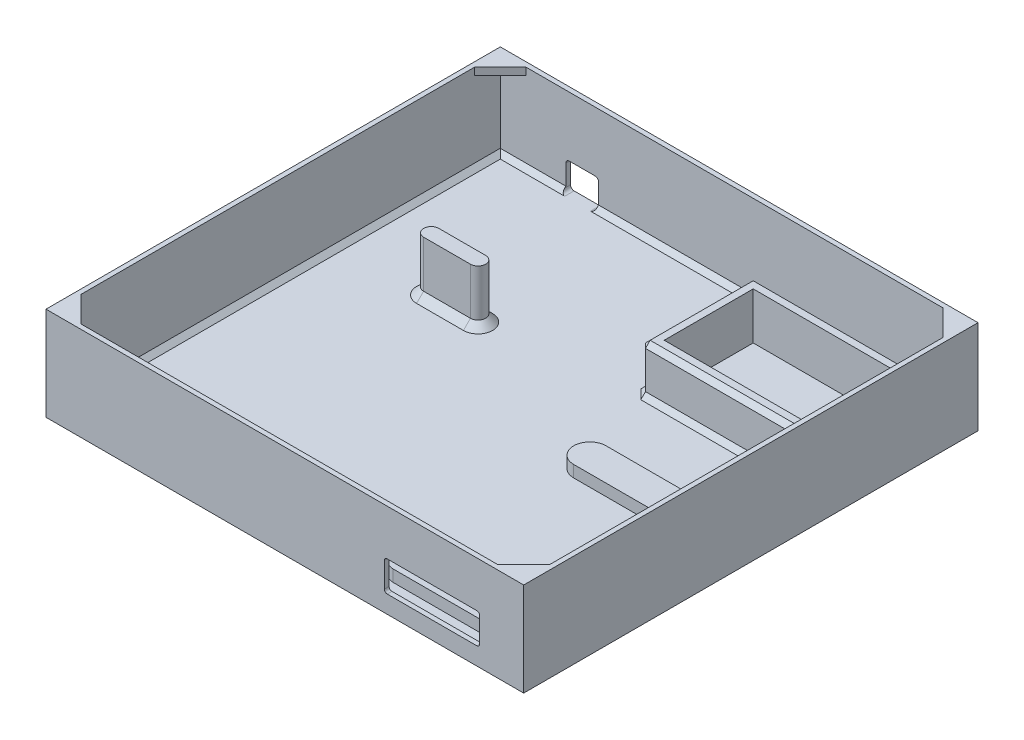
SolidWorks part; units mm, degrees
ref_plane "Ön Düzlem" through (0, 0, 0) normal (0, 0, 1) x (1, 0, 0)
ref_plane "Üst Düzlem" through (0, 0, 0) normal (0, 1, 0) x (1, 0, 0)
ref_plane "Sağ Düzlem" through (0, 0, 0) normal (1, 0, 0) x (0, 0, -1)
sketch "Çizim1" plane through (0, 0, 0) normal (0, 1, 0) x (1, 0, 0)
  line L6 (-102, 97) -> (102, 97)
  line L11 (-102, 97) -> (-102, -97)
  line L12 (-102, -97) -> (102, -97)
  line L17 (102, 97) -> (102, -97)
  line L18 (-102, 97) -> (102, -97) construction
  line L23 (-102, -97) -> (102, 97) construction
  point P0 (0, 0)
  dimension "D1" = 204
  dimension "D2" = 194
extrude "Yükseklik-Ekstrüzyon2" add sketch "Çizim1" along normal blind 40 contours L11 L12 L17 L6
sketch "Çizim3" plane through (0, 40, 0) normal (0, 1, 0) x (1, 0, 0)
  line L1 (-100, 95) -> (100, 95)
  line L2 (-100, 95) -> (-100, -95)
  line L3 (-100, -95) -> (100, -95)
  line L4 (100, 95) -> (100, -95)
  line L5 (-100, 95) -> (100, -95) construction
  line L6 (-100, -95) -> (100, 95) construction
  point P0 (0, 0)
  dimension "D1" = 190
  dimension "D2" = 200
extrude "Kes-Ekstrüzyon2" cut sketch "Çizim3" against normal blind 37.5 contours L2 L3 L4 L1
sketch "Çizim4" plane through (0, 2.5, 0) normal (0, 1, 0) x (1, 0, 0)
  line L0 (-102, 97) -> (-102, -97) construction
  line L1 (-102, -97) -> (102, -97) construction
  line L2 (-62.5, 24.75) -> (-42.5, 24.75)
  line L3 (-62.5, 31.25) -> (-42.5, 31.25)
  line L4 (-42.5, 28) -> (-42.5, -84) construction
  line L5 (-62.5, -87.25) -> (-42.5, -87.25)
  line L6 (-75.9536, -28) -> (-42.5, -28) construction
  line L7 (-62.5, -80.75) -> (-42.5, -80.75)
  arc A5 (-62.5, 31.25) -> (-62.5, 24.75) centre (-62.5, 28) ccw
  arc A7 (-42.5, 24.75) -> (-42.5, 31.25) centre (-42.5, 28) ccw
  arc A10 (-42.5, -80.75) -> (-42.5, -87.25) centre (-42.5, -84) cw
  arc A11 (-62.5, -87.25) -> (-62.5, -80.75) centre (-62.5, -84) cw
  dimension "D3" = 20
  dimension "D4" = 121.75
  dimension "D5" = 6.5
  dimension "D11" = 6.5
  dimension "D12" = 6.5
  dimension "D14" = 20
  dimension "D15" = 3.25
  dimension "D1" = 39.5
  dimension "D2" = 13
extrude "Yükseklik-Ekstrüzyon3" add sketch "Çizim4" along normal blind 23
sketch "Çizim6" plane through (0, 2.5, 0) normal (0, 1, 0) x (1, 0, 0)
  line L0 (-102, 97) -> (102, 97) construction
  line L1 (24, 79) -> (84, 79)
  line L2 (24, 79) -> (24, 41)
  line L3 (24, 41) -> (84, 41)
  line L4 (84, 79) -> (84, 41)
  line L5 (24, 79) -> (84, 41) construction
  line L6 (24, 41) -> (84, 79) construction
  line L7 (19, 84) -> (89, 84)
  line L8 (19, 84) -> (19, 36)
  line L9 (19, 36) -> (89, 36)
  line L10 (89, 84) -> (89, 36)
  line L11 (19, 84) -> (89, 36) construction
  line L12 (19, 36) -> (89, 84) construction
  line L13 (102, 97) -> (102, -97) construction
  point P0 (54, 60)
  point P5 (54, 60)
  dimension "D1" = 38
  dimension "D2" = 60
  dimension "D3" = 70
  dimension "D4" = 5
  dimension "D5" = 13
  dimension "D6" = 13
extrude "Yükseklik-Ekstrüzyon4" add sketch "Çizim6" along normal blind 20
sketch "Çizim7" plane through (0, 2.5, 0) normal (0, 1, 0) x (1, 0, 0)
  line L0 (-102, -97) -> (102, -97) construction
  line L1 (87, -97) -> (33, -97) construction
  line L5 (35.6, -9.25) -> (84.4, -9.25)
  line L8 (84.4, 4.55) -> (35.6, 4.55)
  line L10 (35.6, -77.25) -> (84.4, -77.25)
  line L12 (84.4, -86.45) -> (35.6, -86.45)
  arc A8 (35.6, 4.55) -> (35.6, -9.25) centre (35.6, -2.35) ccw
  arc A9 (84.4, -9.25) -> (84.4, 4.55) centre (84.4, -2.35) ccw
  arc A10 (35.6, -77.25) -> (35.6, -86.45) centre (35.6, -81.85) ccw
  arc A11 (84.4, -86.45) -> (84.4, -77.25) centre (84.0289, -81.85) ccw
  point P2 (83.6578, -86.45)
  point P6 (83.6578, -86.45)
  dimension "D3" = 0
extrude "Yükseklik-Ekstrüzyon7" add sketch "Çizim7" along normal blind 5
sketch "Çizim8" plane through (0, 40, 0) normal (0, 1, 0) x (1, 0, 0)
  line L0 (-102, 97) -> (-102, 82)
  line L1 (-102, 97) -> (-102, -97) construction
  line L2 (-102, 82) -> (-87, 97)
  line L3 (-102, 97) -> (102, 97) construction
  line L4 (-102, 97) -> (-87, 97)
  line L5 (0, 0) -> (166.3911, 0) construction
  line L7 (0, 122.3397) -> (0, 0) construction
  line L8 (102, 97) -> (87, 97)
  line L9 (102, 82) -> (87, 97)
  line L10 (102, 97) -> (102, 82)
  line L11 (102, -97) -> (102, -82)
  line L12 (102, -82) -> (87, -97)
  line L13 (102, -97) -> (87, -97)
  line L14 (-102, -97) -> (-87, -97)
  line L15 (-102, -82) -> (-87, -97)
  line L16 (-102, -97) -> (-102, -82)
  point P21 (0, 0)
  point P22 (0, 0)
  dimension "D1" = 15
  dimension "D2" = 15
extrude "Yükseklik-Ekstrüzyon8" add sketch "Çizim8" against normal blind 3
sketch "Çizim9" plane through (0, 0, 97) normal (0, 0, 1) x (1, 0, 0)
  line L6 (-102, 40) -> (-102, 0) construction
  line L7 (43.7, 7.5) -> (82, 7.5)
  line L8 (42.5, 8.7) -> (42.5, 19.3)
  line L9 (43.7, 20.5) -> (82, 20.5)
  line L10 (83.2, 8.7) -> (83.2, 19.3)
  line L11 (-102, 0) -> (102, 0) construction
  arc A4 (82, 20.5) -> (83.2, 19.3) centre (82, 19.3) cw
  arc A5 (83.2, 8.7) -> (82, 7.5) centre (82, 8.7) cw
  arc A6 (43.7, 7.5) -> (42.5, 8.7) centre (43.7, 8.7) cw
  arc A7 (42.5, 19.3) -> (43.7, 20.5) centre (43.7, 19.3) cw
  dimension "D4" = 40.7
  dimension "D5" = 1.2
  dimension "D1" = 144.5
  dimension "D2" = 7.5
  dimension "D3" = 13
extrude "Kes-Ekstrüzyon5" cut sketch "Çizim9" against normal blind 3
sketch "Çizim11" plane through (0, 0, -97) normal (0, 0, -1) x (-1, 0, 0)
  line L0 (102, 40) -> (102, 0) construction
  line L1 (59.5, 2.5) -> (70.5, 2.5)
  line L2 (58, 4) -> (58, 13)
  line L3 (59.5, 14.5) -> (70.5, 14.5)
  line L4 (72, 4) -> (72, 13)
  line L5 (102, 0) -> (-102, 0) construction
  arc A0 (70.5, 2.5) -> (72, 4) centre (70.5, 4) ccw
  arc A1 (58, 13) -> (59.5, 14.5) centre (59.5, 13) cw
  arc A2 (70.5, 14.5) -> (72, 13) centre (70.5, 13) cw
  arc A3 (59.5, 2.5) -> (58, 4) centre (59.5, 4) cw
  point P10 (72, 2.5)
  point P13 (58, 14.5)
  point P16 (72, 14.5)
  dimension "D5" = 1.5
  dimension "D1" = 14
  dimension "D2" = 12
  dimension "D3" = 30
  dimension "D4" = 2.5
extrude "Kes-Ekstrüzyon7" cut sketch "Çizim11" against normal blind 3
chamfer "Pah1" distance 2 angle 45 19 edges at (0, 2.5, 95) (-100, 2.5, 0) (-85.25, 2.5, -95) (100, 2.5, 0) (20.25, 2.5, -95) (-58.4393, 2.9393, -95) (-71.5607, 2.9393, -95) (89, 22.5, -60) (54, 22.5, -84) (19, 22.5, -60) (54, 22.5, -36) (89, 2.5, -60) (89, 12.5, -36) (54, 2.5, -84) (89, 12.5, -84) (19, 2.5, -60) (19, 12.5, -84) (54, 2.5, -36) (19, 12.5, -36)
chamfer "Pah2" distance 3 angle 45 8 edges at (-39.25, 2.5, 84) (-52.5, 2.5, 80.75) (-65.75, 2.5, 84) (-52.5, 2.5, 87.25) (-65.75, 2.5, -28) (-52.5, 2.5, -24.75) (-39.25, 2.5, -28) (-52.5, 2.5, -31.25)
